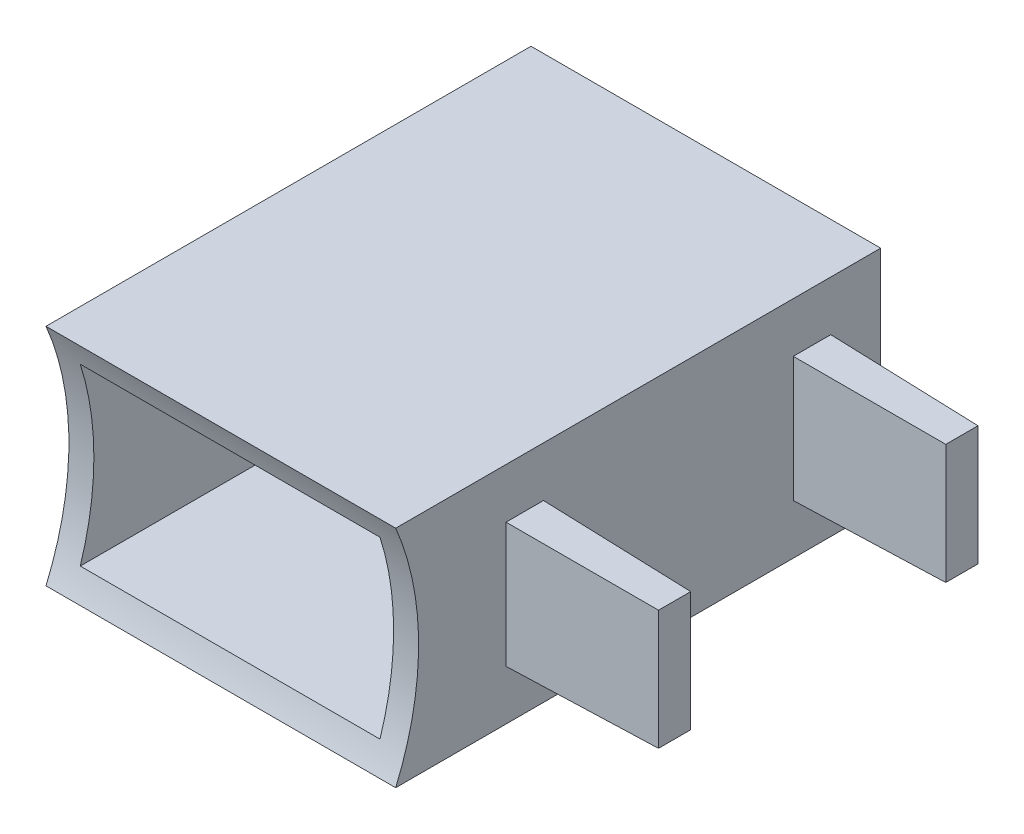
SolidWorks part; units mm, degrees
ref_plane "Front Plane" through (0, 0, 0) normal (0, 0, 1) x (1, 0, 0)
ref_plane "Top Plane" through (0, 0, 0) normal (0, 1, 0) x (1, 0, 0)
ref_plane "Right Plane" through (0, 0, 0) normal (1, 0, 0) x (0, 0, -1)
sketch "Sketch9" plane through (0, 0, 0) normal (0, 1, 0) x (1, 0, 0)
  line L1 (-6, 3.5) -> (6, 3.5)
  line L2 (-6, 3.5) -> (-6, -3.5)
  line L3 (-6, -3.5) -> (6, -3.5)
  line L4 (6, 3.5) -> (6, -3.5)
  line L5 (-6, 3.5) -> (6, -3.5) construction
  line L6 (-6, -3.5) -> (6, 3.5) construction
  point P0 (0, 0)
  dimension "D1" = 7
  dimension "D2" = 12
extrude "Boss-Extrude5" add sketch "Sketch9" along normal blind 25
shell "Shell6" thickness 1
sketch "Sketch12" plane through (7, 0, 0) normal (1, 0, 0) x (0, 0, -1)
  circle A0 centre (0, 0) radius 11.5
  dimension "D1" = 23
extrude "Cut-Extrude2" cut sketch "Sketch12" against normal up to next
sketch "Sketch14" plane through (0, 25, 0) normal (0, 1, 0) x (1, 0, 0)
  line L1 (-7, 4.5) -> (7, 4.5)
  line L2 (-7, 4.5) -> (-7, -4.5)
  line L3 (-7, -4.5) -> (7, -4.5)
  line L4 (7, 4.5) -> (7, -4.5)
  line L5 (-7, 4.5) -> (7, -4.5) construction
  line L6 (-7, -4.5) -> (7, 4.5) construction
  line L7 (-6, 3.5) -> (6, 3.5)
  line L8 (-6, 3.5) -> (-6, -3.5)
  line L9 (-6, -3.5) -> (6, -3.5)
  line L10 (6, 3.5) -> (6, -3.5)
  line L11 (-6, 3.5) -> (6, -3.5) construction
  line L12 (-6, -3.5) -> (6, 3.5) construction
  point P0 (0, 0)
  point P5 (0, 0)
extrude "Boss-Extrude6" add sketch "Sketch14" along normal blind 5
chamfer "Chamfer2" distance 0.5 angle 60 4 edges at (-6, 30, 0) (0, 30, 3.5) (6, 30, 0) (0, 30, -3.5)
sketch "Sketch16" plane through (7, 0, 0) normal (1, 0, 0) x (0, 0, -1)
  line L0 (-4.5, 30) -> (4.5, 30) construction
  line L1 (-2.5, 28) -> (2.5, 28)
  line L2 (-2.5, 28) -> (-2.5, 26.5)
  line L3 (-2.5, 26.5) -> (2.5, 26.5)
  line L4 (2.5, 28) -> (2.5, 26.5)
  line L5 (-2.5, 28) -> (2.5, 26.5) construction
  line L6 (-2.5, 26.5) -> (2.5, 28) construction
  line L7 (-2.5, 16.5) -> (2.5, 16.5)
  line L8 (-2.5, 16.5) -> (-2.5, 15)
  line L9 (-2.5, 15) -> (2.5, 15)
  line L10 (2.5, 16.5) -> (2.5, 15)
  line L11 (-2.5, 16.5) -> (2.5, 15) construction
  line L12 (-2.5, 15) -> (2.5, 16.5) construction
  point P0 (0, 27.25)
  point P5 (0, 15.75)
  point P12 (0, 0)
  point P13 (0, 0)
  dimension "D1" = 1.5
  dimension "D2" = 5
  dimension "D3" = 1.5
  dimension "D4" = 5
  dimension "D5" = 10
  dimension "D6" = 2
extrude "Boss-Extrude7" add sketch "Sketch16" along normal blind 6 draft 1
move or copy body "Body-Move/Copy1" bodies to move or copy 111 copy no rotation origin (0, 20.2915, 0) rotation axis (-1, 0, 0) rotation angle 90
